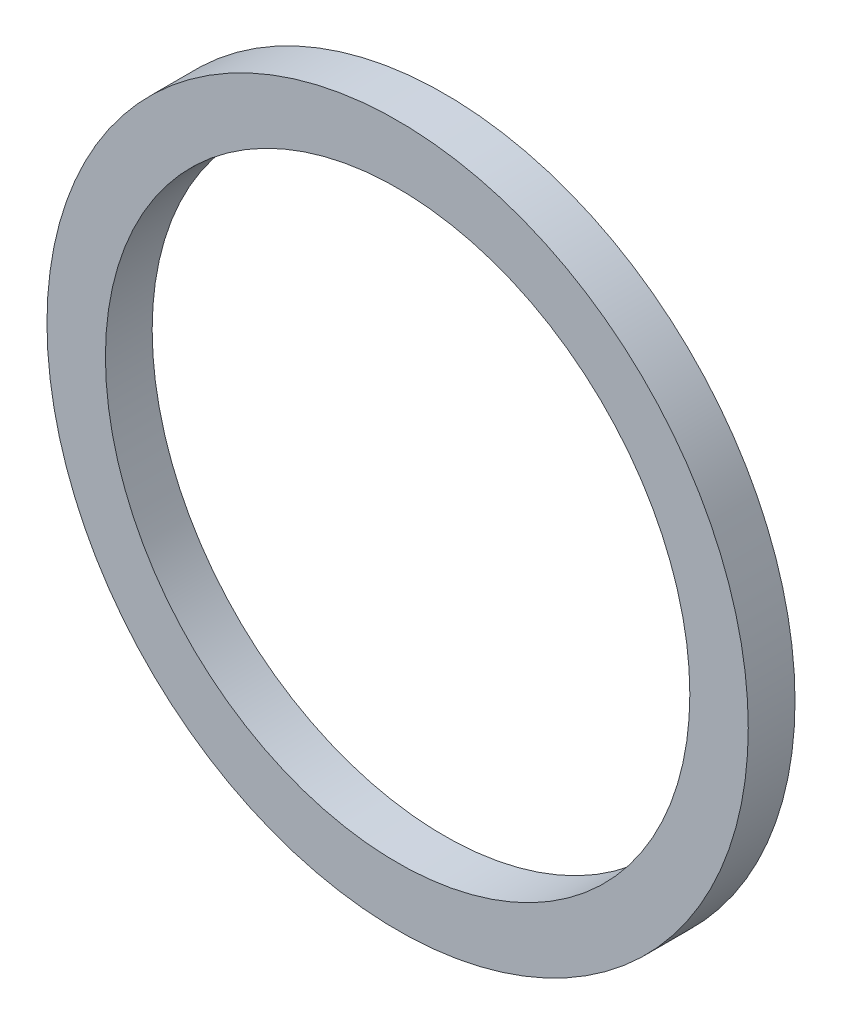
SolidWorks part; units mm, degrees
material "AISI 4130 Steel, normalized at 870C"
ref_plane "Front Plane" through (0, 0, 0) normal (0, 0, 1) x (1, 0, 0)
ref_plane "Top Plane" through (0, 0, 0) normal (0, 1, 0) x (1, 0, 0)
ref_plane "Right Plane" through (0, 0, 0) normal (1, 0, 0) x (0, 0, -1)
sketch "Sketch1" plane through (0, 0, 0) normal (0, 0, 1) x (1, 0, 0)
  circle A0 centre (0, 0) radius 15
  circle A1 centre (0, 0) radius 12.5
  dimension "D1" = 25
  dimension "D2" = 30
extrude "Boss-Extrude1" add sketch "Sketch1" along normal blind 2
